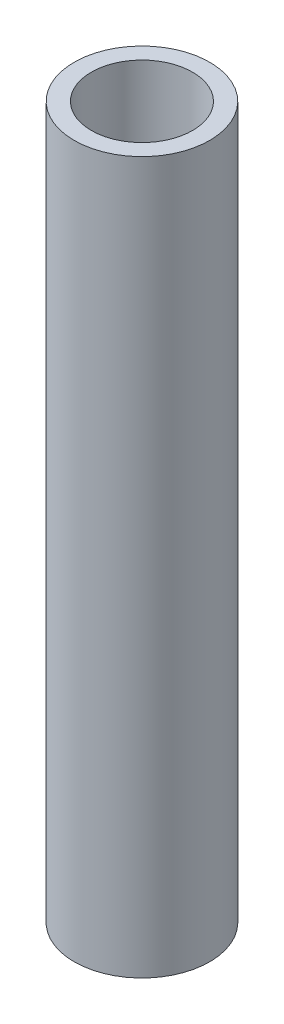
SolidWorks part; units mm, degrees
ref_plane "Front Plane" through (0, 0, 0) normal (0, 0, 1) x (1, 0, 0)
ref_plane "Top Plane" through (0, 0, 0) normal (0, 1, 0) x (1, 0, 0)
ref_plane "Right Plane" through (0, 0, 0) normal (1, 0, 0) x (0, 0, -1)
sketch "Sketch1" plane through (0, 0, 0) normal (0, 1, 0) x (1, 0, 0)
  circle A0 centre (0, 0) radius 9.525
  circle A1 centre (0, 0) radius 7.112
  dimension "D1" = 19.05
  dimension "D2" = 2.413
extrude "Boss-Extrude1" add sketch "Sketch1" along normal blind 100
